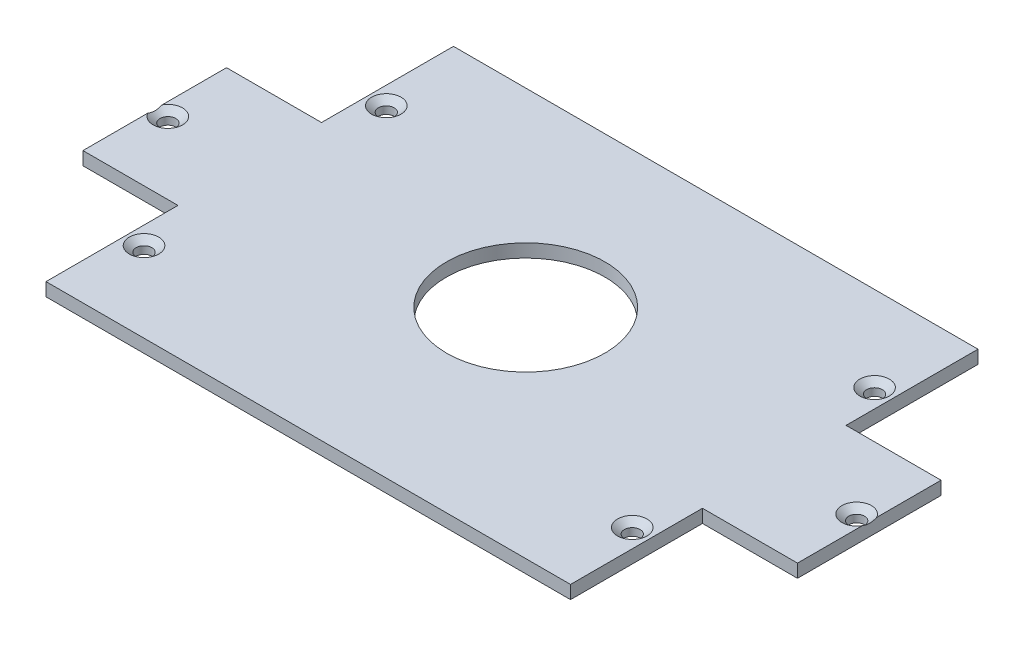
SolidWorks part; units mm, degrees
material "6061-T6 (SS)"
ref_plane "Front Plane" through (0, 0, 0) normal (0, 0, 1) x (1, 0, 0)
ref_plane "Top Plane" through (0, 0, 0) normal (0, 1, 0) x (1, 0, 0)
ref_plane "Right Plane" through (0, 0, 0) normal (1, 0, 0) x (0, 0, -1)
sketch "Sketch1" plane through (0, 0, 0) normal (0, 1, 0) x (1, 0, 0)
  line L0 (-63.8996, 57.6907) -> (62.3067, 57.6907)
  line L1 (62.3067, -40.3533) -> (-63.8996, -40.3533)
  line L2 (-63.8996, 57.6907) -> (-63.8996, 25.9407)
  line L4 (62.3067, 57.6907) -> (62.3067, 25.9407)
  line L9 (-63.8996, -8.6033) -> (-63.8996, -40.3533)
  line L11 (62.3067, 25.9407) -> (85.1667, 25.9407)
  line L13 (62.3067, -8.6033) -> (85.1667, -8.6033)
  line L14 (85.1667, 25.9407) -> (85.1667, -8.6033)
  line L15 (-63.8996, -8.6033) -> (-86.7596, -8.6033)
  line L17 (-63.8996, 25.9407) -> (-86.7596, 25.9407)
  line L18 (-86.7596, -8.6033) -> (-86.7596, 25.9407)
  line L19 (62.3067, -8.6033) -> (62.3067, -40.3533)
  circle A0 centre (-0.7965, 11.9707) radius 19.05
  point P0 (0, 0)
  dimension "D5" = 63.1031
  dimension "D7" = 38.1
  dimension "D6" = 45.72
  dimension "D1" = 126.2062
  dimension "D2" = 31.75
  dimension "D3" = 34.544
  dimension "D4" = 22.86
  dimension "D8" = 40.3533
extrude "Boss-Extrude1" add sketch "Sketch1" along normal blind 3.175
hole_wizard "CSK for #6 Flat Head Machine Screw (100)1" positions "Sketch3" profile "Sketch2" countersink size "#6" standard "ANSI Inch" end condition through all
sketch "Sketch3" plane through (0, 3.175, 0) normal (0, 1, 0) x (1, 0, 0)
  point P0 (-59.6133, 37.2466)
  point P3 (-59.6133, -21.0541)
  point P6 (57.8617, -21.0541)
  point P9 (57.8617, 37.2466)
sketch "Sketch2" plane through (-59.6133, 3.175, -37.2466) normal (1, 0, 0) x (0, 0, 1)
  line L0 (0, 0) -> (0, 3.175)
  line L1 (0, 3.175) -> (1.8986, 3.175)
  line L2 (1.8986, 3.175) -> (1.8986, 1.38)
  line L3 (1.8986, 1.38) -> (3.5433, 0)
  line L5 (3.5433, 0) -> (0, 0)
  line L6 (-1.8987, 1.38) -> (-3.5433, 0) construction
  line L11 (0, -6.35) -> (0, 107.95) construction
  dimension "Thru Hole Dia." = 3.7973
  dimension "Thru Hole Depth" = 3.175
  dimension "Near C'Sink Dia." = 7.0866
  dimension "Near C'Sink Angle" = 100
hole_wizard "CSK for #6 Flat Head Machine Screw (100)2" positions "Sketch6" profile "Sketch7" countersink size "#6" standard "ANSI Inch" end condition through all
sketch "Sketch6" plane through (0, 3.175, 0) normal (0, 1, 0) x (1, 0, 0)
  point P0 (82.071, 8.7313)
  point P3 (82.071, 8.7313)
  point P5 (-83.664, 8.7313)
sketch "Sketch7" plane through (82.071, 3.175, -8.7313) normal (1, 0, 0) x (0, 0, 1)
  line L0 (0, 0) -> (0, 3.175)
  line L1 (0, 3.175) -> (1.8986, 3.175)
  line L2 (1.8986, 3.175) -> (1.8986, 1.38)
  line L3 (1.8986, 1.38) -> (3.5433, 0)
  line L5 (3.5433, 0) -> (0, 0)
  line L6 (-1.8986, 1.38) -> (-3.5433, 0) construction
  line L11 (0, -6.35) -> (0, 107.95) construction
  dimension "Thru Hole Dia." = 3.7973
  dimension "Thru Hole Depth" = 3.175
  dimension "Near C'Sink Dia." = 7.0866
  dimension "Near C'Sink Angle" = 100
equation "\"D5@Sketch1\"=\"D1@Sketch1\"/2"
